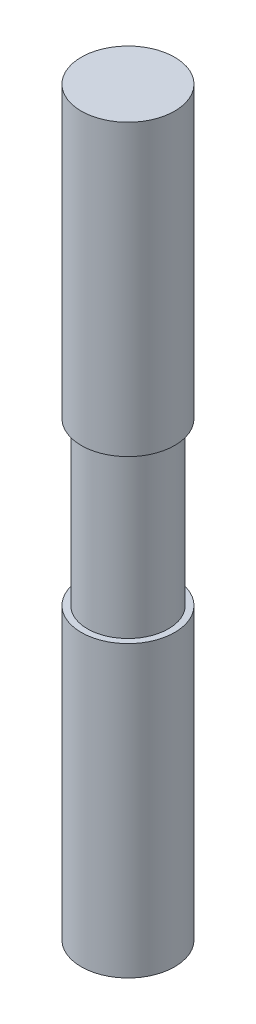
SolidWorks part; units mm, degrees
material "AISI 4340 Steel, annealed"
ref_plane "Front Plane" through (0, 0, 0) normal (0, 0, 1) x (1, 0, 0)
ref_plane "Top Plane" through (0, 0, 0) normal (0, 1, 0) x (1, 0, 0)
ref_plane "Right Plane" through (0, 0, 0) normal (1, 0, 0) x (0, 0, -1)
sketch "Sketch2" plane through (0, 0, 0) normal (0, 1, 0) x (1, 0, 0)
  circle A0 centre (0, 0) radius 4.7625
  dimension "D1" = 9.525
extrude "Boss-Extrude1" add sketch "Sketch2" along normal blind 75.565
cosmetic thread "Cosmetic Thread1"
ref_plane "Plane1" through (0, 37.7825, 0) normal (0, 1, 0) x (1, 0, 0)
sketch "Sketch3" plane through (0, 37.7825, 0) normal (0, 1, 0) x (1, 0, 0)
  circle A0 centre (0, 0) radius 4.1275
  dimension "D1" = 8.255
extrude "Cut-Extrude1" cut sketch "Sketch3" against normal blind 8.255 and the other way blind 8.255 flip side to cut
